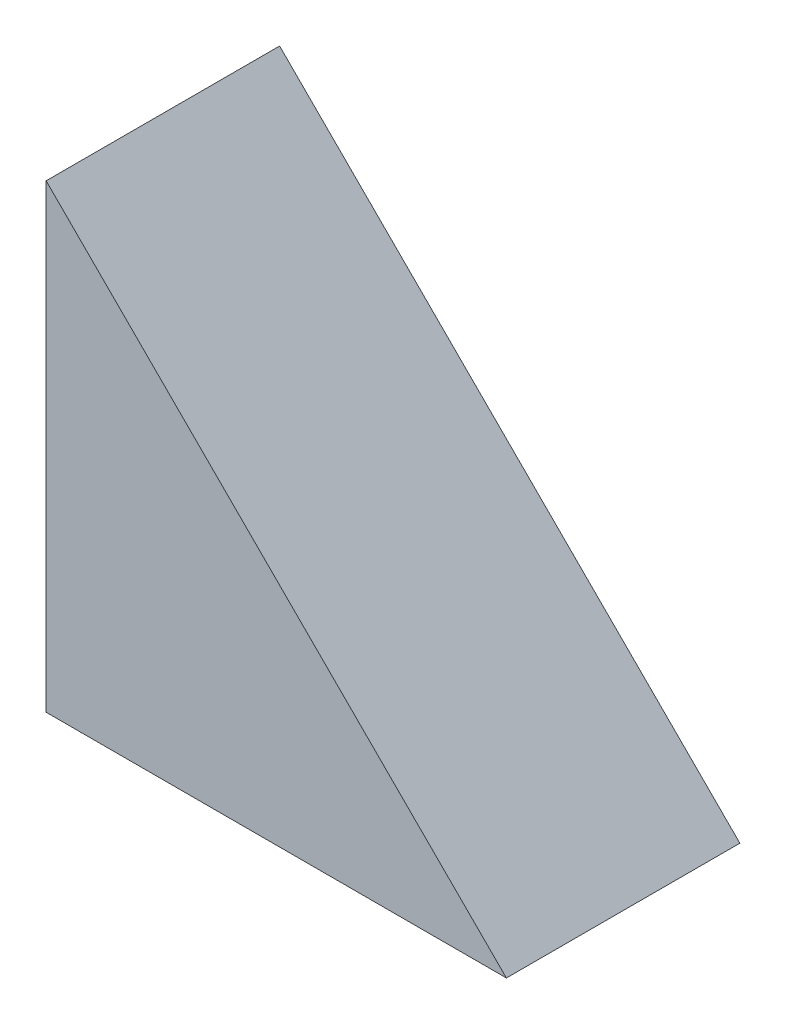
SolidWorks part; units mm, degrees
ref_plane "Front Plane" through (0, 0, 0) normal (0, 0, 1) x (1, 0, 0)
ref_plane "Top Plane" through (0, 0, 0) normal (0, 1, 0) x (1, 0, 0)
ref_plane "Right Plane" through (0, 0, 0) normal (1, 0, 0) x (0, 0, -1)
sketch "Sketch1" plane through (0, 0, 0) normal (0, 0, 1) x (1, 0, 0)
  line L0 (0, 0) -> (69, 0)
  line L1 (69, 0) -> (0, 69)
  line L2 (0, 69) -> (0, 0)
  dimension "D1" = 69
extrude "Boss-Extrude1" add sketch "Sketch1" along normal blind 35
